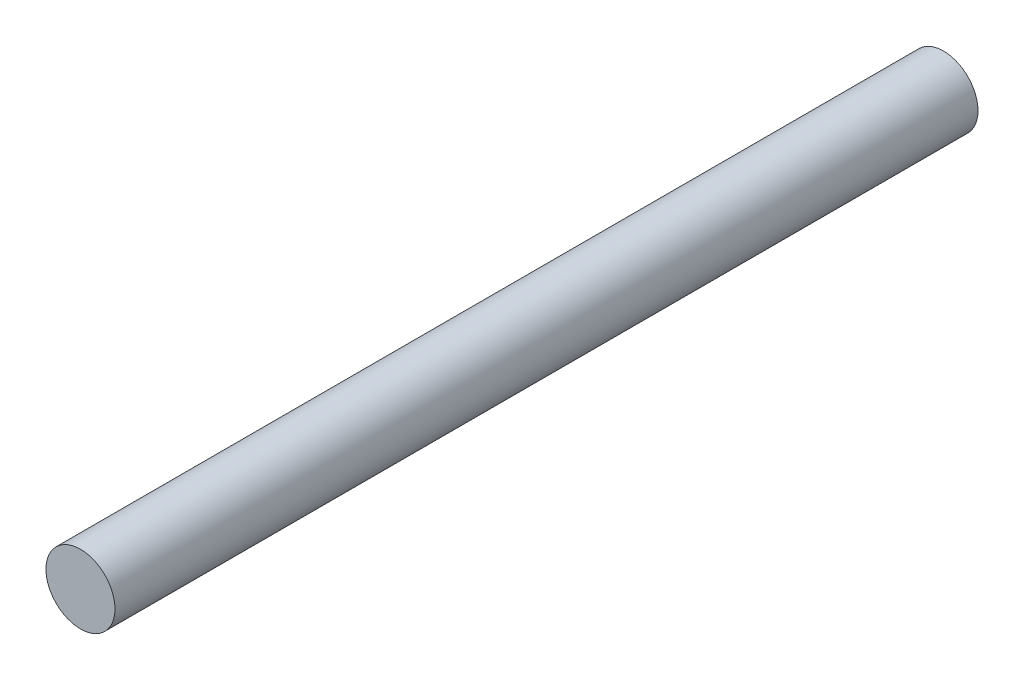
SolidWorks part; units mm, degrees
ref_plane "Front Plane" through (0, 0, 0) normal (0, 0, 1) x (1, 0, 0)
ref_plane "Top Plane" through (0, 0, 0) normal (0, 1, 0) x (1, 0, 0)
ref_plane "Right Plane" through (0, 0, 0) normal (1, 0, 0) x (0, 0, -1)
sketch "Sketch2" plane through (0, 0, 0) normal (0, 0, 1) x (1, 0, 0)
  circle A0 centre (0, 0) radius 4
extrude "Boss-Extrude1" add sketch "Sketch2" against normal blind 100
